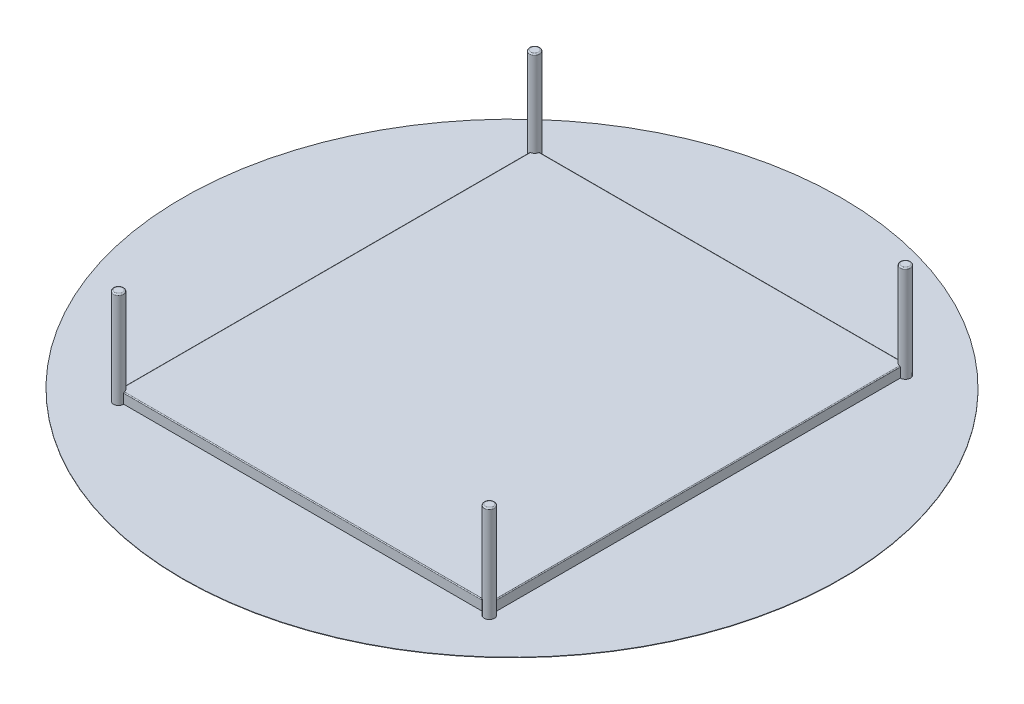
SolidWorks part; units mm, degrees
ref_plane "Front Plane" through (0, 0, 0) normal (0, 0, 1) x (1, 0, 0)
ref_plane "Top Plane" through (0, 0, 0) normal (0, 1, 0) x (1, 0, 0)
ref_plane "Right Plane" through (0, 0, 0) normal (1, 0, 0) x (0, 0, -1)
sketch "Sketch1" plane through (0, 0, 0) normal (0, 1, 0) x (1, 0, 0)
  circle A0 centre (0, 0) radius 800
  dimension "D1" = 1600
extrude "Boss-Extrude1" add sketch "Sketch1" along normal blind 1
sketch "Sketch2" plane through (0, 1, 0) normal (0, 1, 0) x (1, 0, 0)
  line L1 (-450, -505) -> (450, -505)
  line L2 (-450, -505) -> (-450, 505)
  line L3 (-450, 505) -> (450, 505)
  line L4 (450, -505) -> (450, 505)
  line L5 (-450, -505) -> (450, 505) construction
  line L6 (-450, 505) -> (450, -505) construction
  point P0 (0, 0)
  dimension "D1" = 900
  dimension "D2" = 1010
extrude "Boss-Extrude2" add sketch "Sketch2" along normal blind 25 separate body
sketch "Sketch3" plane through (0, 1, 0) normal (0, 1, 0) x (1, 0, 0)
  circle A0 centre (-450, -505) radius 12.5
  circle A1 centre (450, -505) radius 12.5
  circle A2 centre (450, 505) radius 12.5
  circle A3 centre (-450, 505) radius 12.5
  dimension "D1" = 25
extrude "Boss-Extrude3" add sketch "Sketch3" along normal blind 234
fillet "Fillet2" radius 2 4 edges at (0, 26, 505) (-450, 26, 0) (0, 26, -505) (450, 26, 0)
fillet "Fillet3" radius 3 4 edges at (450, 235, 517.5) (-450, 235, 517.5) (450, 235, -492.5) (-450, 235, -492.5)
